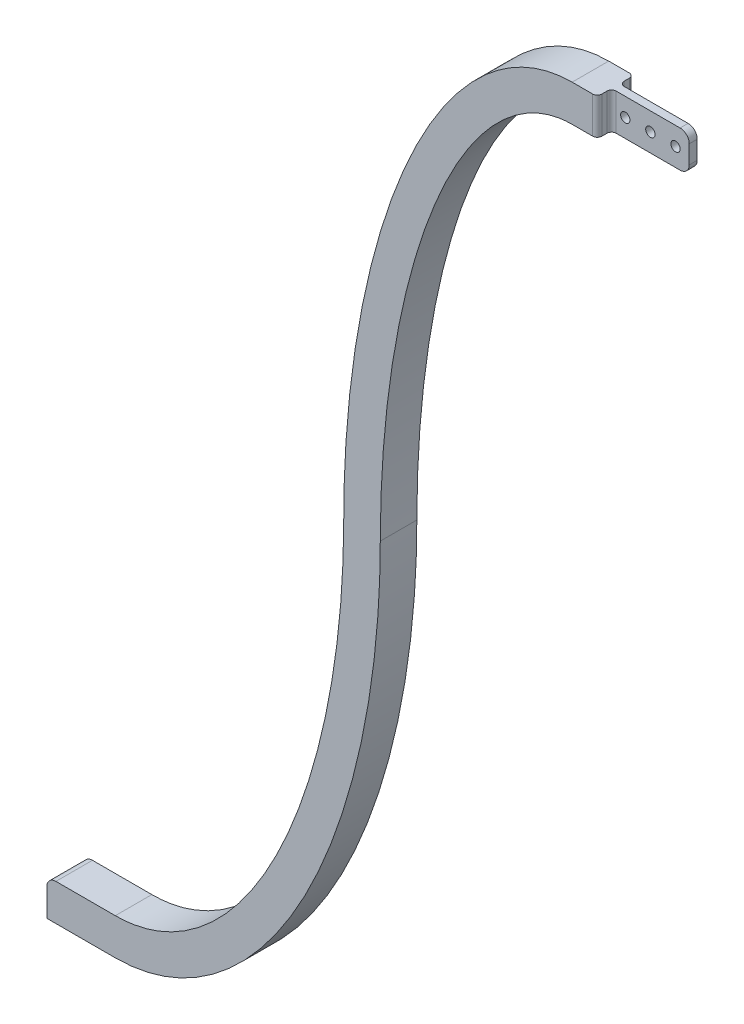
SolidWorks part; units mm, degrees
ref_plane "Front Plane" through (0, 0, 0) normal (0, 0, 1) x (1, 0, 0)
ref_plane "Top Plane" through (0, 0, 0) normal (0, 1, 0) x (1, 0, 0)
ref_plane "Right Plane" through (0, 0, 0) normal (1, 0, 0) x (0, 0, -1)
sketch "Sketch1" plane through (0, 0, 0) normal (0, 0, 1) x (1, 0, 0)
  line L15 (50, 0) -> (0, 0) construction
  line L16 (0, 0) -> (-50, 0) construction
  line L17 (-50, 0) -> (-50, -100) construction
  line L18 (50, 100) -> (50, 0) construction
  line L25 (-50, -100) -> (-65, -100)
  line L27 (-50, -108) -> (-65, -108)
  line L28 (-65, -100) -> (-65, -108)
  line L29 (50, 108) -> (72.5, 108)
  line L31 (50, 100) -> (72.5, 100)
  line L32 (72.5, 108) -> (72.5, 100)
  ellipse E0 centre (50, 0) end of major axis (50, -108) minor radius 50 (50, 108) -> (0, 0) ccw
  ellipse E1 centre (-50, 0) end of major axis (-50, 100) minor radius 50 (-50, -100) -> (0, 0) ccw
  ellipse E2 centre (-50, 0) end of major axis (-50, -108) minor radius 58 (-50, -108) -> (8, 0) ccw
  ellipse E3 centre (50, 0) end of major axis (50, 100) minor radius 42 (50, 100) -> (8, 0) ccw
  dimension "D1" = 8
  dimension "D2" = 8
  dimension "D3" = 100
  dimension "D4" = 50
  dimension "D5" = 15
  dimension "D6" = 8
  dimension "D7" = 22.5
extrude "Boss-Extrude1" add sketch "Sketch1" along normal mid plane 8
sketch "Sketch2" plane through (0, 0, 4) normal (0, 0, 1) x (1, 0, 0)
  line L0 (72.5, 100) -> (72.5, 108) construction
  line L1 (64, 104) -> (69.5, 104) construction
  line L2 (69.5, 104) -> (72.5, 104) construction
  line L3 (64, 104) -> (58.5, 104) construction
  circle A0 centre (69.5, 104) radius 1.025
  circle A1 centre (64, 104) radius 1.025
  circle A2 centre (58.5, 104) radius 1.025
  dimension "D1" = 3
  dimension "D2" = 5.5
  dimension "D3" = 2.05
extrude "Cut-Extrude1" cut sketch "Sketch2" against normal through all
fillet "Fillet1" radius 2 3 edges at (-65, -100, 0) (72.5, 100, 0) (72.5, 108, 0)
sketch "Sketch3" plane through (0, 0, 4) normal (0, 0, 1) x (1, 0, 0)
  line L0 (50, 100) -> (70.5, 100) construction
  line L1 (55.5, 108) -> (72.5, 108)
  line L2 (55.5, 108) -> (55.5, 100)
  line L3 (55.5, 100) -> (72.5, 100)
  line L4 (72.5, 108) -> (72.5, 100)
  line L5 (72.5, 102) -> (72.5, 106) construction
  dimension "D1" = 17
extrude "Cut-Extrude2" cut sketch "Sketch3" against normal blind 3.125
mirror "Mirror1" about plane through (0, 0, 0) normal (0, 0, 1) of "Cut-Extrude2"
fillet "Fillet7" radius 1 4 edges at (55.5, 104, 4) (55.5, 104, -4) (55.5, 104, -0.875) (55.5, 104, 0.875)
equation "\"D1@Sketch1\"=\"D2@Sketch1\""
equation "\"D4@Sketch1\"=\"D3@Sketch1\"*0.5"
equation "\"D7@Sketch1\"=\"D5@Sketch1\"*3/2"
